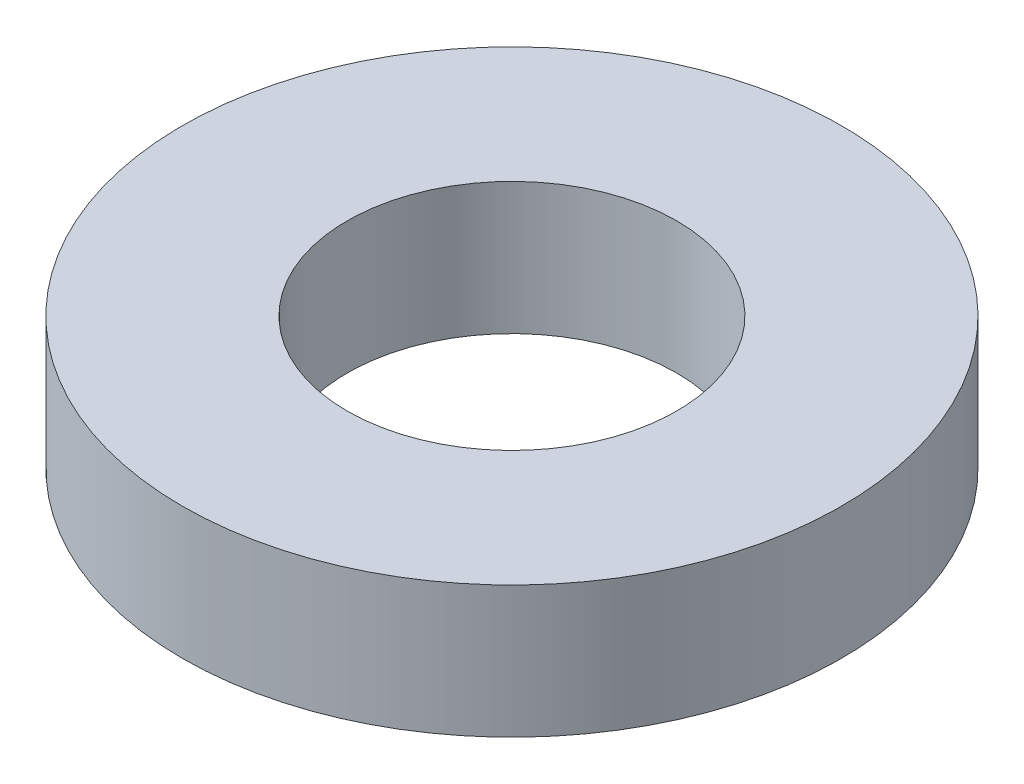
SolidWorks part; units mm, degrees
ref_plane "Front Plane" through (0, 0, 0) normal (0, 0, 1) x (1, 0, 0)
ref_plane "Top Plane" through (0, 0, 0) normal (0, 1, 0) x (1, 0, 0)
ref_plane "Right Plane" through (0, 0, 0) normal (1, 0, 0) x (0, 0, -1)
sketch "Sketch1" plane through (0, 0, 0) normal (0, 1, 0) x (1, 0, 0)
  circle A0 centre (0, 0) radius 3.175
  circle A1 centre (0, 0) radius 6.35
  dimension "D1" = 6.35
  dimension "D2" = 12.7
extrude "Boss-Extrude1" add sketch "Sketch1" along normal blind 2.54
